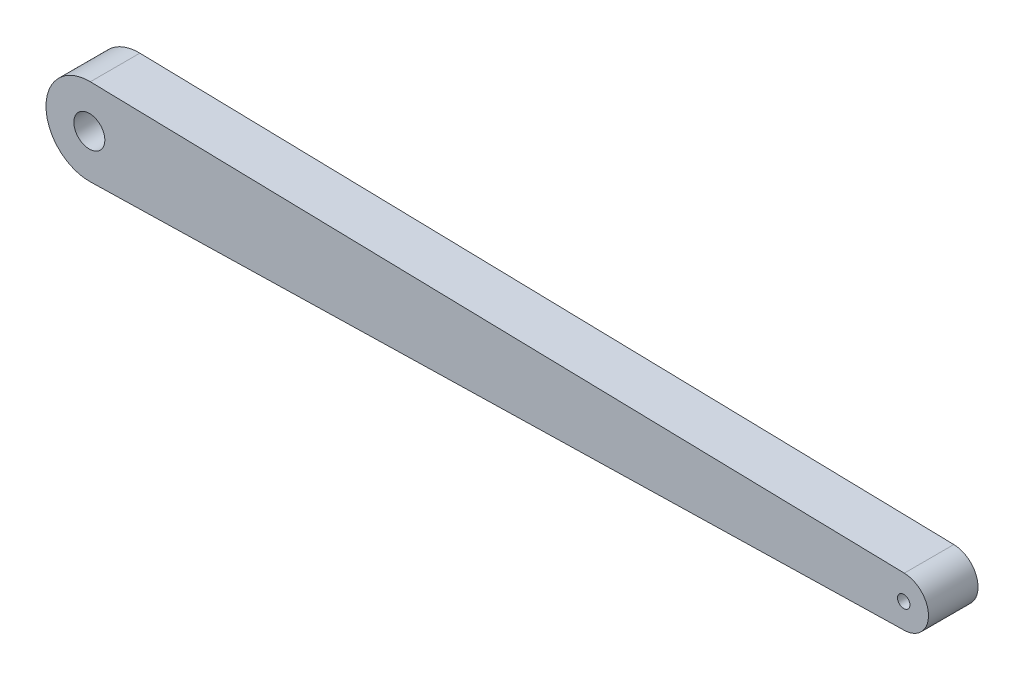
SolidWorks part; units mm, degrees
ref_plane "Front Plane" through (0, 0, 0) normal (0, 0, 1) x (1, 0, 0)
ref_plane "Top Plane" through (0, 0, 0) normal (0, 1, 0) x (1, 0, 0)
ref_plane "Right Plane" through (0, 0, 0) normal (1, 0, 0) x (0, 0, -1)
sketch "Sketch1" plane through (0, 0, 0) normal (0, 0, 1) x (1, 0, 0)
  line L0 (-982.1731, 79.4822) -> (332.1425, 49.4901)
  line L1 (-982.1731, -60.4813) -> (332.1425, -30.4891)
  arc A0 (-982.1731, 79.4822) -> (-982.1731, -60.4813) centre (-983.77, 9.5004) ccw
  arc A1 (332.1425, -30.4891) -> (332.1425, 49.4901) centre (331.23, 9.5005) ccw
  circle A2 centre (-983.77, 9.5004) radius 25
  circle A3 centre (331.23, 9.5005) radius 10
  point P7 (-1053.77, 9.5004)
  point P9 (371.23, 9.5005)
  dimension "D1" = 70
  dimension "D2" = 50
  dimension "D3" = 40
  dimension "D4" = 20
  dimension "D5" = 1425
  dimension "D6" = 1315
extrude "Boss-Extrude1" add sketch "Sketch1" along normal mid plane 80
